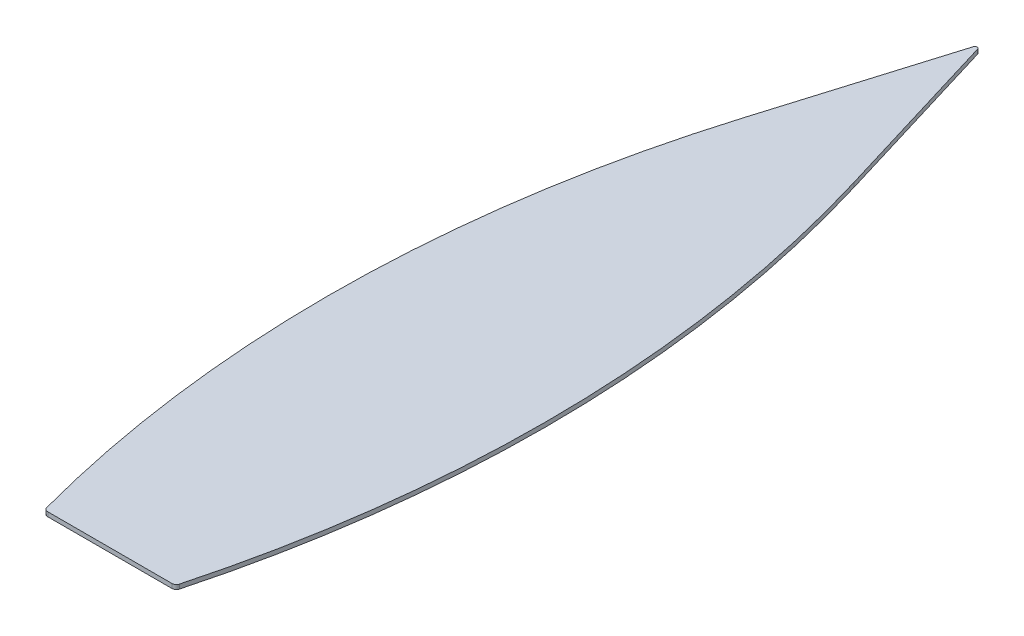
SolidWorks part; units mm, degrees
material "AISI 304"
ref_plane "Front" through (0, 0, 0) normal (0, 0, 1) x (1, 0, 0)
ref_plane "Top" through (0, 0, 0) normal (0, 1, 0) x (1, 0, 0)
ref_plane "Right" through (0, 0, 0) normal (1, 0, 0) x (0, 0, -1)
sketch "Sketch1" plane through (0, 0, 0) normal (0, 1, 0) x (1, 0, 0)
  line L0 (0, -500) -> (0, 500) construction
  line L1 (-75, -500) -> (75, -500)
  line L2 (-63.7134, 289.3389) -> (0, 500)
  line L3 (0, 500) -> (63.7134, 289.3389)
  line L4 (-125, -125) -> (125, -125) construction
  arc A0 (-75, -500) -> (-63.7134, 289.3389) centre (1306.25, -125) cw
  arc A1 (63.7134, 289.3389) -> (75, -500) centre (-1306.25, -125) cw
  point P4 (0, 0)
  point P8 (0, -500)
  dimension "D3" = 250
  dimension "D1" = 1000
  dimension "D2" = 150
  dimension "D4" = 375
extrude "Boss-Extrude1" add sketch "Sketch1" along normal blind 5
fillet "Fillet1" radius 5 2 edges at (-75, 2.5, 500) (75, 2.5, 500)
fillet "Fillet2" radius 2.5 1 edges at (0, 2.5, -500)
